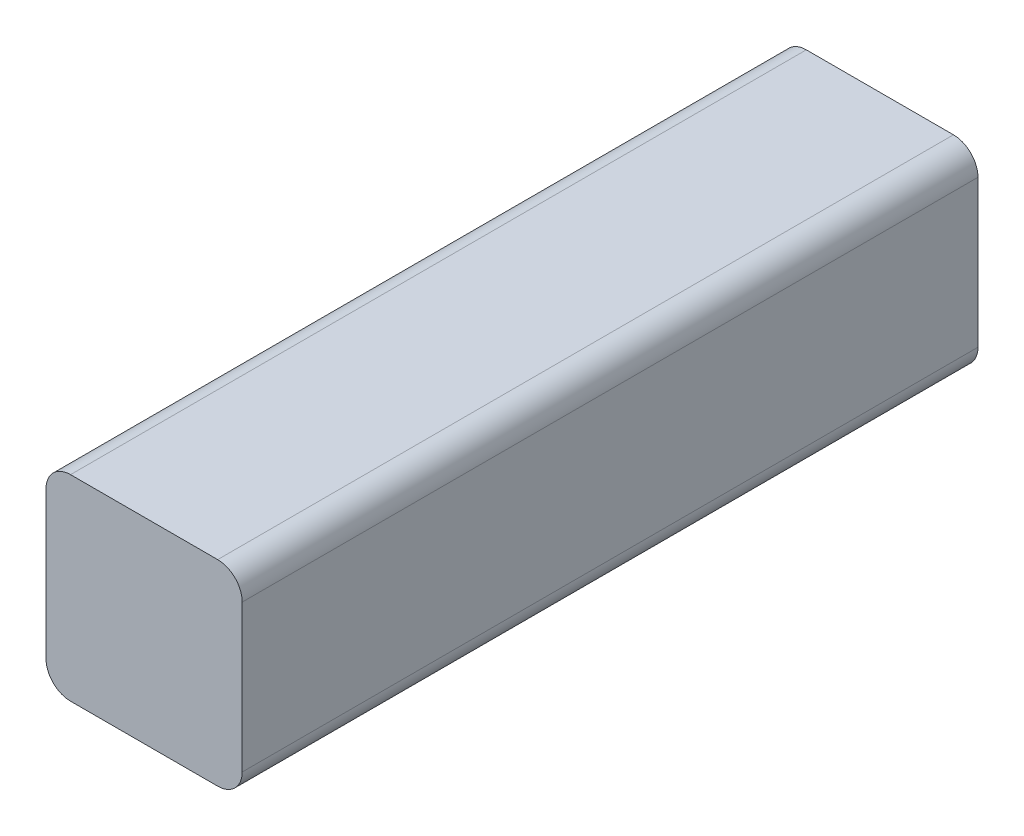
SolidWorks part; units mm, degrees
ref_plane "Front Plane" through (0, 0, 0) normal (0, 0, 1) x (1, 0, 0)
ref_plane "Top Plane" through (0, 0, 0) normal (0, 1, 0) x (1, 0, 0)
ref_plane "Right Plane" through (0, 0, 0) normal (1, 0, 0) x (0, 0, -1)
sketch "Sketch1" plane through (0, 0, 0) normal (0, 0, 1) x (1, 0, 0)
  line L0 (75.3595, -63) -> (-74.6405, -63) construction
  line L1 (20, -63) -> (-20, -63)
  line L2 (20, -63) -> (20, -23)
  line L3 (20, -23) -> (-20, -23)
  line L4 (-20, -63) -> (-20, -23)
  line L5 (20, -63) -> (-20, -23) construction
  line L6 (20, -23) -> (-20, -63) construction
  point P4 (0, -43)
  dimension "D1" = 40
extrude "Boss-Extrude1" add sketch "Sketch1" along normal blind 150
fillet "Fillet1" radius 5 4 edges at (20, -23, 75) (20, -63, 75) (-20, -23, 75) (-20, -63, 75)
ref_plane "Plane1" through (0, -43, 0) normal (0, 1, 0) x (1, 0, 0)
